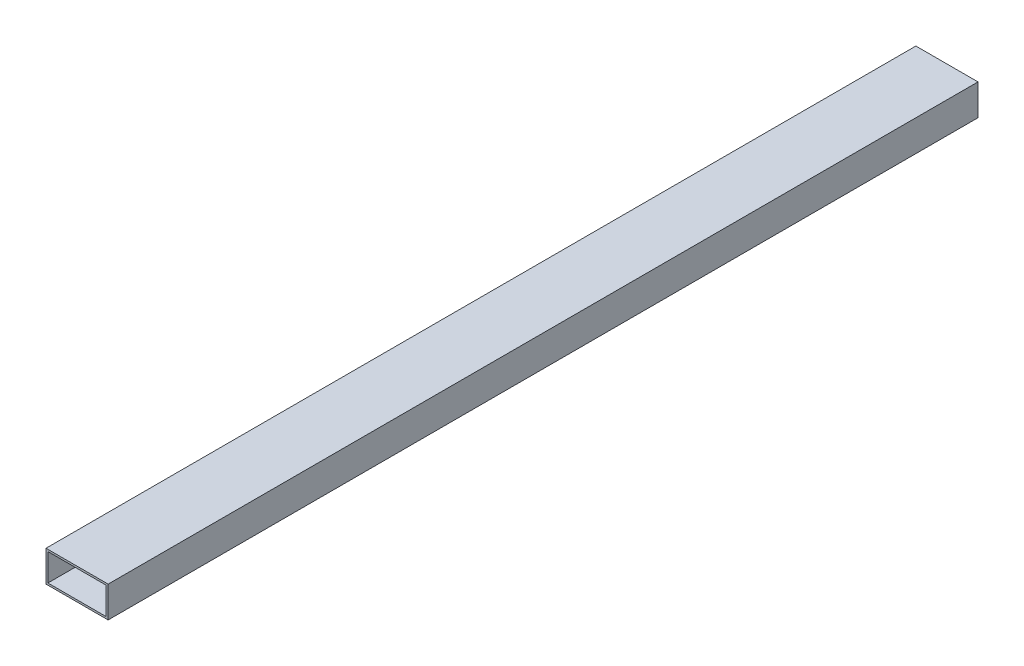
SolidWorks part; units mm, degrees
ref_plane "Front Plane" through (0, 0, 0) normal (0, 0, 1) x (1, 0, 0)
ref_plane "Top Plane" through (0, 0, 0) normal (0, 1, 0) x (1, 0, 0)
ref_plane "Right Plane" through (0, 0, 0) normal (1, 0, 0) x (0, 0, -1)
sketch "Sketch1" plane through (0, 0, 0) normal (0, 0, 1) x (1, 0, 0)
  line L1 (-35.2408, -1.1304) -> (15.5592, -1.1304)
  line L2 (-35.2408, -1.1304) -> (-35.2408, 24.2696)
  line L3 (-35.2408, 24.2696) -> (15.5592, 24.2696)
  line L4 (15.5592, -1.1304) -> (15.5592, 24.2696)
  dimension "D1" = 50.8
  dimension "D2" = 25.4
extrude "Extrude-Thin1" add sketch "Sketch1" along normal blind 711.2 thin thin type one direction reverse wall 1.5748
